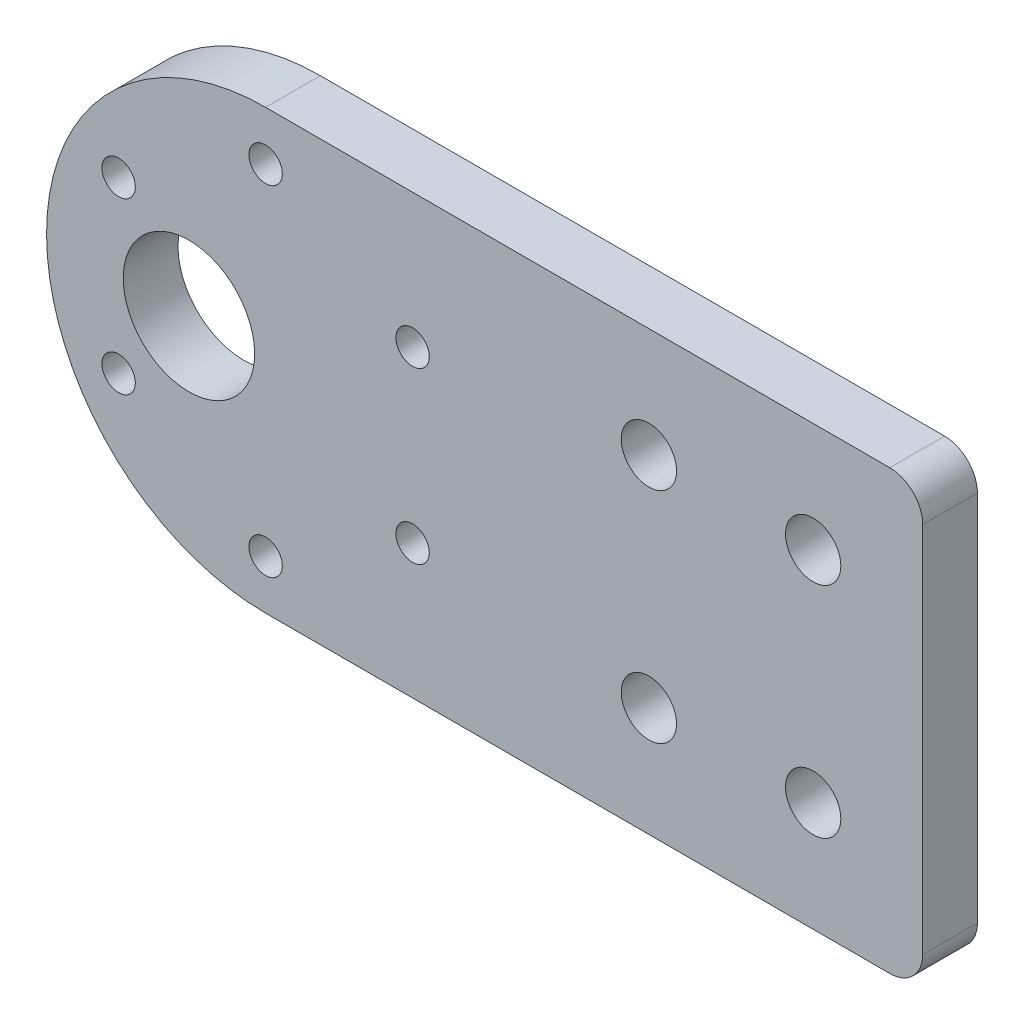
SolidWorks part; units mm, degrees
ref_plane "Front Plane" through (0, 0, 0) normal (0, 0, 1) x (1, 0, 0)
ref_plane "Top Plane" through (0, 0, 0) normal (0, 1, 0) x (1, 0, 0)
ref_plane "Right Plane" through (0, 0, 0) normal (1, 0, 0) x (0, 0, -1)
sketch "Sketch1" plane through (0, 0, 0) normal (0, 0, 1) x (1, 0, 0)
  line L0 (0, 0) -> (0, 40)
  line L1 (0, 40) -> (80, 40)
  line L2 (80, 40) -> (80, 0)
  line L3 (80, 0) -> (0, 0)
  dimension "D1" = 80
  dimension "D2" = 40
extrude "Boss-Extrude1" add sketch "Sketch1" along normal blind 5
sketch "Sketch10" plane through (0, 0, 5) normal (0, 0, 1) x (1, 0, 0)
  line L0 (80, 40) -> (0, 40) construction
  line L1 (0, 40) -> (0, 0) construction
  line L3 (0, 40) -> (20, 40)
  line L4 (0, 40) -> (0, 0)
  line L5 (0, 0) -> (20, 0)
  arc A0 (20, 40) -> (20, 0) centre (20, 20) ccw
  line M4 (0, 0) -> (80, 0)
  line M6 (80, 40) -> (0, 40)
  line M7 (0, 40) -> (0, 0)
  dimension "D1" = 40
  dimension "D2" = 20
  dimension "D3" = 20
extrude "Cut-Extrude4" cut sketch "Sketch10" against normal up to next contours A0 L4 M4 | A0 M6 M7
sketch "Sketch11" plane through (0, 0, 5) normal (0, 0, 1) x (1, 0, 0)
  line L0 (80, 0) -> (80, 40) construction
  line L1 (20, 0) -> (80, 0) construction
  line L2 (80, 40) -> (20, 40) construction
  circle A0 centre (55, 30) radius 2.525
  circle A1 centre (70, 30) radius 2.525
  circle A2 centre (55, 10) radius 2.525
  circle A3 centre (70, 10) radius 2.525
  dimension "D1" = 5.05
  dimension "D2" = 5.05
  dimension "D3" = 5.05
  dimension "D4" = 5.05
  dimension "D5" = 15
  dimension "D6" = 15
  dimension "D7" = 10
  dimension "D8" = 10
  dimension "D9" = 10
  dimension "D10" = 10
  dimension "D11" = 10
  dimension "D12" = 10
extrude "Cut-Extrude5" cut sketch "Sketch11" against normal up to next
fillet "Fillet1" radius 3 2 edges at (80, 0, 2.5) (80, 40, 2.5)
sketch "Sketch19" plane through (0, 0, 5) normal (0, 0, 1) x (1, 0, 0)
  circle A2 centre (20, 35.5) radius 1.525
  circle A3 centre (33.4234, 27.75) radius 1.525
  circle A5 centre (33.4234, 12.25) radius 1.525
  circle A7 centre (20, 4.5) radius 1.525
  circle A9 centre (6.5766, 12.25) radius 1.525
  circle A11 centre (6.5766, 27.75) radius 1.525
  circle A13 centre (13, 20) radius 6
  point P26 (20, 20)
  dimension "D1" = 3.05
  dimension "D4" = 3.05
  dimension "D5" = 3.05
  dimension "D6" = 6
  dimension "D7" = 12
  dimension "D2" = 3.05
  dimension "D3" = 3.05
  dimension "D8" = 3.05
extrude "Cut-Extrude9" cut sketch "Sketch19" against normal up to next
